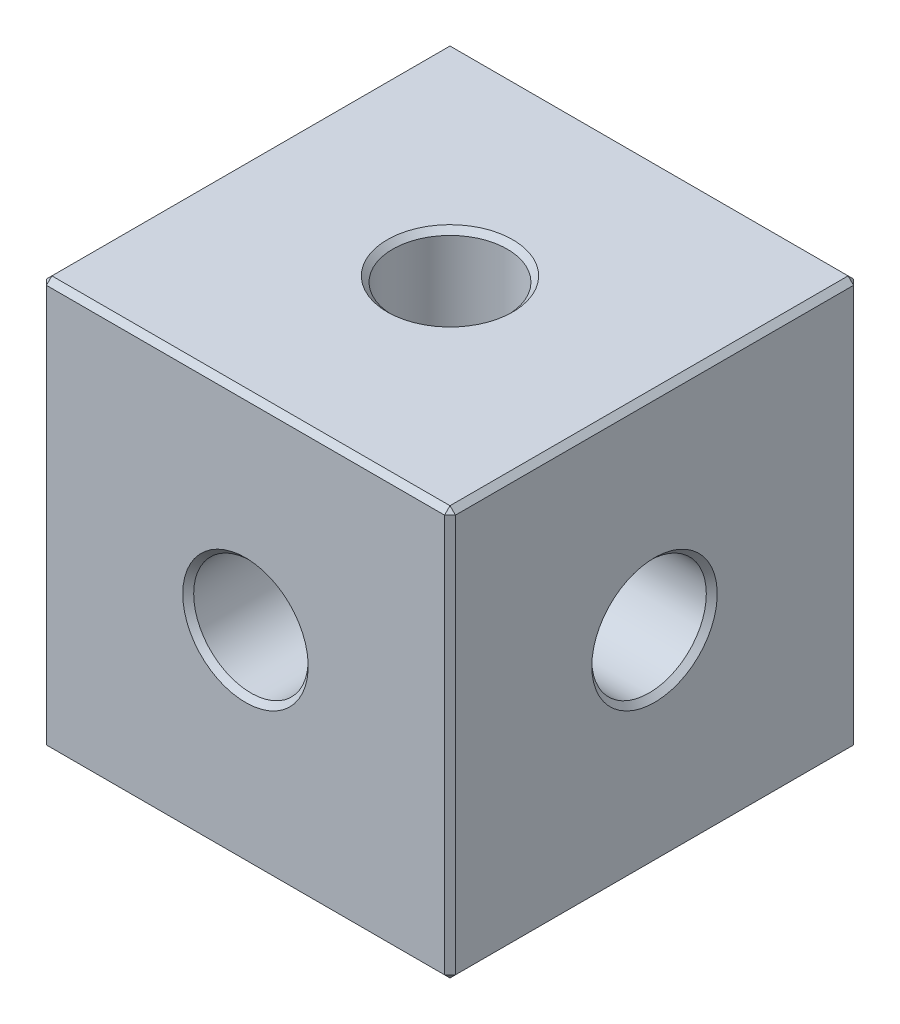
SolidWorks part; units mm, degrees
ref_plane "前视基准面" through (0, 0, 0) normal (0, 0, 1) x (1, 0, 0)
ref_plane "上视基准面" through (0, 0, 0) normal (0, 1, 0) x (1, 0, 0)
ref_plane "右视基准面" through (0, 0, 0) normal (1, 0, 0) x (0, 0, -1)
sketch "草图1" plane through (0, 0, 0) normal (0, 1, 0) x (1, 0, 0)
  line L1 (-7.5, 7.5) -> (7.5, 7.5)
  line L2 (-7.5, 7.5) -> (-7.5, -7.5)
  line L3 (-7.5, -7.5) -> (7.5, -7.5)
  line L4 (7.5, 7.5) -> (7.5, -7.5)
  line L5 (-7.5, 7.5) -> (7.5, -7.5) construction
  line L6 (-7.5, -7.5) -> (7.5, 7.5) construction
  point P0 (0, 0)
  dimension "D1" = 15
extrude "凸台-拉伸1" add sketch "草图1" along normal mid plane 15
hole_wizard "M5 螺纹孔1" positions "草图2" profile "草图3" tap size "M5" standard "GB" end condition through all
sketch "草图2" plane through (0, 0, 7.5) normal (0, 0, 1) x (1, 0, 0)
  point P0 (0, 0)
sketch "草图3" plane through (0, 0, 7.5) normal (1, 0, 0) x (0, -1, 0)
  line L0 (0, 0) -> (0, 15)
  line L1 (0, 15) -> (2.1, 15)
  line L2 (2.1, 15) -> (2.1, 0)
  line L5 (2.1, 0) -> (0, 0)
  line L11 (0, -6.35) -> (0, 107.95) construction
  dimension "通孔螺纹孔钻头直径" = 4.2
  dimension "通孔螺纹孔钻头深度" = 15
cosmetic thread "孔螺蚊线1"
hole_wizard "M5 螺纹孔2" positions "草图4" profile "草图5" tap size "M5" standard "GB" end condition through all
sketch "草图4" plane through (0, 7.5, 0) normal (0, 1, 0) x (1, 0, 0)
  point P0 (0, 0)
sketch "草图5" plane through (0, 7.5, 0) normal (1, 0, 0) x (0, 0, 1)
  line L0 (0, 0) -> (0, 15)
  line L1 (0, 15) -> (2.1, 15)
  line L2 (2.1, 15) -> (2.1, 0)
  line L5 (2.1, 0) -> (0, 0)
  line L11 (0, -6.35) -> (0, 107.95) construction
  dimension "通孔螺纹孔钻头直径" = 4.2
  dimension "通孔螺纹孔钻头深度" = 15
cosmetic thread "孔螺蚊线2"
hole_wizard "M5 螺纹孔3" positions "草图6" profile "草图7" tap size "M5" standard "GB" end condition through all
sketch "草图6" plane through (7.5, 0, 0) normal (1, 0, 0) x (0, 0, -1)
  point P0 (0, 0)
sketch "草图7" plane through (7.5, 0, 0) normal (0, 1, 0) x (0, 0, -1)
  line L0 (0, 0) -> (0, 15)
  line L1 (0, 15) -> (2.1, 15)
  line L2 (2.1, 15) -> (2.1, 0)
  line L5 (2.1, 0) -> (0, 0)
  line L11 (0, -6.35) -> (0, 107.95) construction
  dimension "通孔螺纹孔钻头直径" = 4.2
  dimension "通孔螺纹孔钻头深度" = 15
cosmetic thread "孔螺蚊线3" parameters "D2"=5
chamfer "倒角1" distance 0.2 angle 45 18 edges at (0, -7.5, 2.1) (-7.5, 0, -2.1) (2.1, 0, -7.5) (7.5, 0, -2.1) (2.1, 0, 7.5) (-7.5, -7.5, 0) (-7.5, 0, -7.5) (0, -7.5, -7.5) (7.5, 0, -7.5) (7.5, -7.5, 0) (-7.5, 0, 7.5) (0, -7.5, 7.5) (7.5, 0, 7.5) (0, 7.5, 7.5) (-7.5, 7.5, 0) (0, 7.5, -7.5) (7.5, 7.5, 0) (0, 7.5, 2.1)
